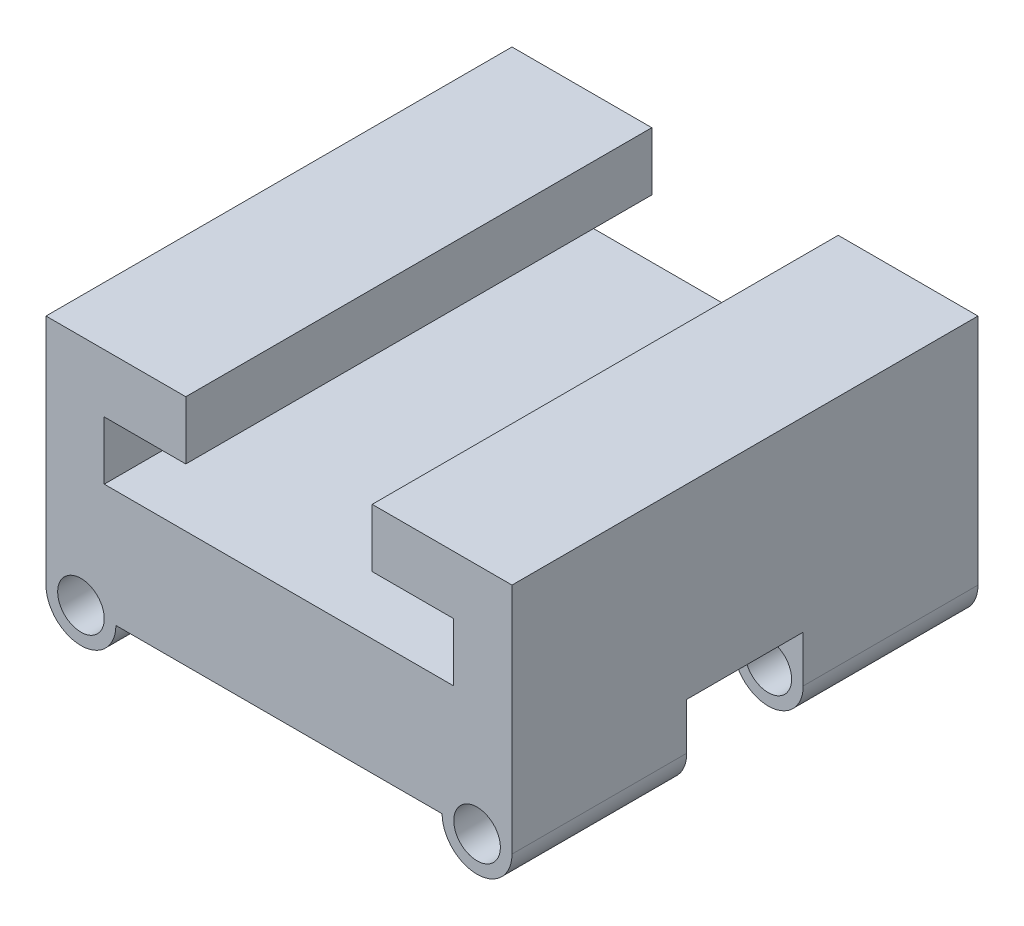
SolidWorks part; units mm, degrees
ref_plane "Front Plane" through (0, 0, 0) normal (0, 0, 1) x (1, 0, 0)
ref_plane "Top Plane" through (0, 0, 0) normal (0, 1, 0) x (1, 0, 0)
ref_plane "Right Plane" through (0, 0, 0) normal (1, 0, 0) x (0, 0, -1)
sketch "Sketch2" plane through (0, 0, 0) normal (0, 0, 1) x (1, 0, 0)
  line L0 (-20, 20) -> (-8, 20)
  line L1 (-8, 20) -> (-8, 15)
  line L2 (-8, 15) -> (-15, 15)
  line L3 (-15, 15) -> (-15, 10)
  line L4 (-15, 10) -> (15, 10)
  line L5 (15, 10) -> (15, 15)
  line L6 (15, 15) -> (8, 15)
  line L7 (8, 15) -> (8, 20)
  line L8 (8, 20) -> (20, 20)
  line L9 (20, 20) -> (20, 0)
  line L10 (20, 0) -> (-20, 0)
  line L11 (-20, 0) -> (-20, 20)
  point P9 (0, 0)
  dimension "D1" = 20
  dimension "D2" = 5
  dimension "D3" = 5
  dimension "D4" = 7
  dimension "D5" = 30
  dimension "D6" = 40
extrude "Boss-Extrude1" add sketch "Sketch2" along normal blind 40 contours L8 L9 L10 L11 L0 L1 L2 L3 L4 L5 L6 L7
sketch "Sketch3" plane through (0, 0, 0) normal (0, 0, -1) x (-1, 0, 0)
  line L0 (-20, 0) -> (20, 0) construction
  line L1 (-20, 0) -> (-14, 0)
  arc A0 (-20, 0) -> (-14, 0) centre (-17, 0) ccw
  dimension "D1" = 6
extrude "Boss-Extrude2" add sketch "Sketch3" against normal blind 15
ref_plane "Plane1" through (0, 0, 20) normal (0, 0, -1) x (-1, 0, 0)
mirror "Mirror1" about plane through (0, 0, 20) normal (0, 0, -1) of "Boss-Extrude2"
ref_plane "Plane2" through (0, 0, 0) normal (-1, 0, 0) x (0, 0, 1)
sketch "Sketch9" plane through (0, 0, 0) normal (0, 0, -1) x (-1, 0, 0)
  line L0 (-14, 0) -> (20, 0) construction
  circle A0 centre (17, 0) radius 3
  dimension "D1" = 6
extrude "Boss-Extrude3" add sketch "Sketch9" against normal up to surface (40 mm away) up to face at (1.0769, 12.0769, 40)
sketch "Sketch10" plane through (0, 0, 25) normal (0, 0, -1) x (-1, 0, 0)
  line L0 (-17, 4) -> (-20, 4)
  line L1 (-20, 20) -> (-20, 0) construction
  line L2 (-20, 4) -> (-20, 2.6458)
  arc A0 (-20, 2.6458) -> (-17, 4) centre (-17, 0) ccw
  arc A1 (-20, 0) -> (-14, 0) centre (-17, 0) ccw construction
  dimension "D1" = 8
extrude "Cut-Extrude2" cut sketch "Sketch10" along normal up to surface (10 mm away) up to face at (17, -1.5, 15)
hole_wizard "Ø4.0 mm Dowel Holes2" positions "Sketch11" profile "Sketch12" hole size "Ø4.0" standard "ISO" end condition through all
sketch "Sketch11" plane through (0, 0, 0) normal (0, 0, -1) x (-1, 0, 0)
  point P0 (-17, 0)
sketch "Sketch12" plane through (17, 0, 0) normal (1, 0, 0) x (0, 1, 0)
  line L0 (0, 0) -> (0, 40)
  line L1 (0, 40) -> (2, 40)
  line L2 (2, 40) -> (2, 0)
  line L5 (2, 0) -> (0, 0)
  line L11 (0, -6.35) -> (0, 107.95) construction
  dimension "Thru Hole Dia." = 4
  dimension "Thru Hole Depth" = 40
mirror "Mirror5" about plane through (0, 0, 0) normal (-1, 0, 0) of "Ø4.0 mm Dowel Holes2"
